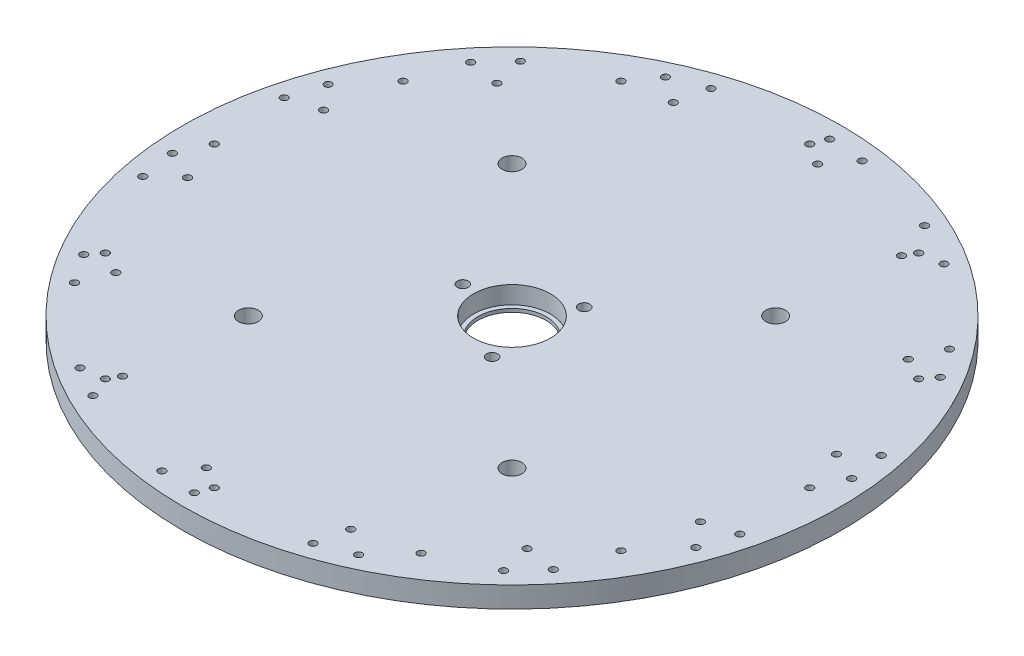
SolidWorks part; units mm, degrees
ref_plane "Front Plane" through (0, 0, 0) normal (0, 0, 1) x (1, 0, 0)
ref_plane "Top Plane" through (0, 0, 0) normal (0, 1, 0) x (1, 0, 0)
ref_plane "Right Plane" through (0, 0, 0) normal (1, 0, 0) x (0, 0, -1)
sketch "Sketch1" plane through (0, 0, 0) normal (0, 1, 0) x (1, 0, 0)
  circle A0 centre (0, 0) radius 150
extrude "Boss-Extrude1" add sketch "Sketch1" along normal blind 9.52
sketch "Sketch2" plane through (0, 9.52, 0) normal (0, 1, 0) x (1, 0, 0)
  circle A0 centre (0, 0) radius 15.5
extrude "Cut-Extrude1" cut sketch "Sketch2" against normal through all
sketch "Sketch3" plane through (0, 9.52, 0) normal (0, 1, 0) x (1, 0, 0)
  circle A0 centre (0, 0) radius 17.505
extrude "Cut-Extrude2" cut sketch "Sketch3" against normal blind 8
sketch "Sketch4" plane through (0, 9.52, 0) normal (0, 1, 0) x (1, 0, 0)
  circle A0 centre (11.6494, -20.6996) radius 2.5
  circle A1 centre (-23.7164, 1.3084) radius 2.5
  circle A2 centre (12.9913, 19.8849) radius 2.5
  circle A3 centre (72.8595, -114.2442) radius 1.65
  circle A4 centre (0, -135.5) radius 1.65
  circle A5 centre (-67.75, -117.3464) radius 1.65
  circle A6 centre (-117.3464, -67.75) radius 1.65
  circle A7 centre (-135.5, 0) radius 1.65
  circle A8 centre (-117.3464, 67.75) radius 1.65
  circle A9 centre (-67.75, 117.3464) radius 1.65
  circle A10 centre (0, 135.5) radius 1.65
  circle A11 centre (67.75, 117.3464) radius 1.65
  circle A12 centre (117.3464, 67.75) radius 1.65
  circle A13 centre (135.5, 0) radius 1.65
  circle A14 centre (117.3464, -67.75) radius 1.65
extrude "Cut-Extrude3" cut sketch "Sketch4" against normal through all
sketch "Sketch6" plane through (0, 0, 0) normal (0, -1, 0) x (-1, 0, 0)
  circle A0 centre (-58.3106, 129.4879) radius 1.65
  circle A1 centre (-77.8212, 118.7902) radius 1.65
  circle A2 centre (-64.893, 112.3979) radius 1.65
  circle A3 centre (-9.6989, 129.423) radius 1.65
  circle A4 centre (-2.618, 141.9873) radius 1.65
  circle A5 centre (-18.5733, 140.7916) radius 1.65
  circle A6 centre (59.2472, 129.0621) radius 1.65
  circle A7 centre (44.3532, 134.9075) radius 1.65
  circle A8 centre (47.4161, 120.8143) radius 1.65
  circle A9 centre (109.3778, 90.5745) radius 1.65
  circle A10 centre (98.4951, 102.3033) radius 1.65
  circle A11 centre (95.1398, 88.2769) radius 1.65
  circle A12 centre (133.1287, 49.4367) radius 1.65
  circle A13 centre (124.0199, 38.2551) radius 1.65
  circle A14 centre (137.8448, 34.1476) radius 1.65
  circle A15 centre (141.3946, -13.2214) radius 1.65
  circle A16 centre (128.3363, -19.3436) radius 1.65
  circle A17 centre (139.01, -29.0427) radius 1.65
  circle A18 centre (121.6556, -73.2609) radius 1.65
  circle A19 centre (112.6425, -86.4808) radius 1.65
  circle A20 centre (107.2342, -73.111) radius 1.65
  circle A21 centre (64.893, -112.3979) radius 1.65
  circle A22 centre (63.9648, -126.7902) radius 1.65
  circle A23 centre (77.8212, -118.7902) radius 1.65
  circle A24 centre (9.6989, -129.423) radius 1.65
  circle A25 centre (2.618, -141.9873) radius 1.65
  circle A26 centre (18.5733, -140.7916) radius 1.65
  circle A27 centre (-44.3532, -134.9075) radius 1.65
  circle A28 centre (-59.2472, -129.0621) radius 1.65
  circle A29 centre (-47.4161, -120.8143) radius 1.65
  circle A30 centre (-98.4951, -102.3033) radius 1.65
  circle A31 centre (-109.3778, -90.5745) radius 1.65
  circle A32 centre (-95.1398, -88.2769) radius 1.65
  circle A33 centre (-124.0199, -38.2551) radius 1.65
  circle A34 centre (-137.8448, -34.1476) radius 1.65
  circle A35 centre (-133.1287, -49.4367) radius 1.65
  circle A36 centre (-128.3363, 19.3436) radius 1.65
  circle A37 centre (-141.3946, 13.2214) radius 1.65
  circle A38 centre (-139.01, 29.0427) radius 1.65
  circle A39 centre (-107.2342, 73.111) radius 1.65
  circle A40 centre (-121.6556, 73.2609) radius 1.65
  circle A41 centre (-112.6425, 86.4808) radius 1.65
extrude "Cut-Extrude5" cut sketch "Sketch6" against normal through all
sketch "Sketch7" plane through (0, 9.52, 0) normal (0, 1, 0) x (1, 0, 0)
  circle A8 centre (-60, -60) radius 4.5
  circle A9 centre (60, -60) radius 4.5
  circle A10 centre (60, 60) radius 4.5
  circle A11 centre (-60, 60) radius 4.5
  dimension "D1" = 2
  dimension "D2" = 2
extrude "Cut-Extrude6" cut sketch "Sketch7" against normal through all
